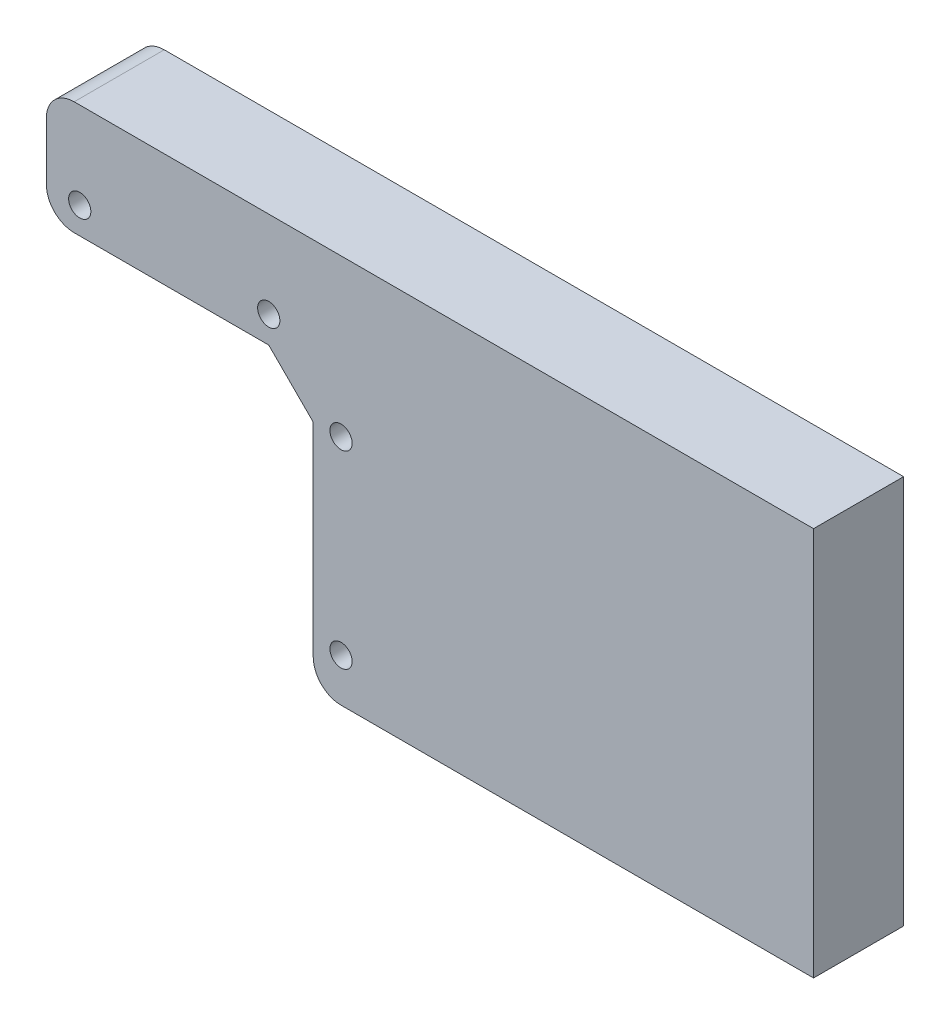
SolidWorks part; units mm, degrees
ref_plane "Plan de face" through (0, 0, 0) normal (0, 0, 1) x (1, 0, 0)
ref_plane "Plan de dessus" through (0, 0, 0) normal (0, 1, 0) x (1, 0, 0)
ref_plane "Plan de droite" through (0, 0, 0) normal (1, 0, 0) x (0, 0, -1)
sketch "Esquisse1" plane through (0, 0, 0) normal (0, 0, 1) x (1, 0, 0)
  line L1 (0, 0) -> (45, 0)
  line L2 (0, 0) -> (0, 35)
  line L3 (0, 35) -> (45, 35)
  line L4 (45, 0) -> (45, 35)
  dimension "D1" = 45
  dimension "D2" = 35
extrude "Boss.-Extru.1" add sketch "Esquisse1" along normal blind 8.1
sketch "Esquisse2" plane through (0, 0, 8.1) normal (0, 0, 1) x (1, 0, 0)
  line L1 (0, 35) -> (-24, 35)
  line L2 (0, 35) -> (0, 24.8)
  line L3 (0, 24.8) -> (-24, 24.8)
  line L4 (-24, 35) -> (-24, 24.8)
  dimension "D1" = 10.2
  dimension "D2" = 24
extrude "Boss.-Extru.2" add sketch "Esquisse2" against normal up to vertex (8.1 mm away) up to point (0, 35, 0)
sketch "Esquisse3" plane through (0, 0, 8.1) normal (0, 0, 1) x (1, 0, 0)
  line L0 (-21, 27.2) -> (-4, 27.2) construction
  line L1 (45, 35) -> (-24, 35) construction
  line L2 (0, 24.8) -> (0, 0) construction
  line L3 (2.5, 3.9) -> (2.5, 20.9) construction
  circle A0 centre (-4, 27.2) radius 1
  circle A1 centre (-21, 27.2) radius 1
  circle A2 centre (2.5, 20.9) radius 1
  circle A4 centre (2.5, 3.9) radius 1
  dimension "D1" = 2
  dimension "D5" = 17
  dimension "D6" = 6.5
  dimension "D7" = 6.3
  dimension "D2" = 7.8
  dimension "D3" = 17
  dimension "D4" = 4
extrude "Enlèv. mat.-Extru.1" cut sketch "Esquisse3" against normal through all
chamfer "Chanfrein1" distance 4 angle 45 1 edges at (0, 24.8, 4.05)
fillet "Congé1" radius 2.5 3 edges at (0, 0, 4.05) (-24, 35, 4.05) (-24, 24.8, 4.05)
